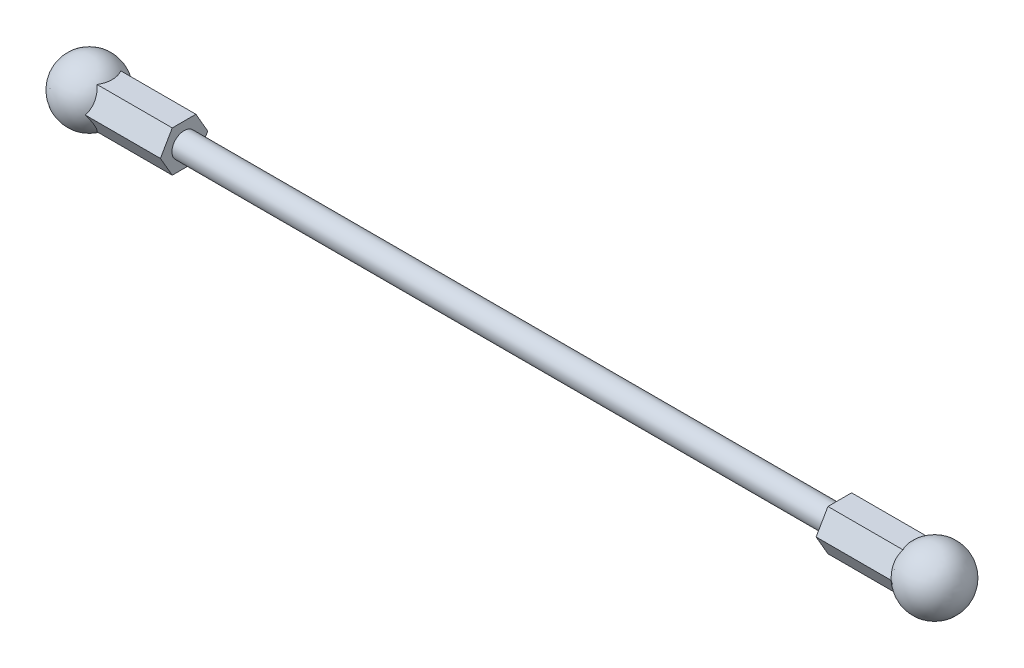
SolidWorks part; units mm, degrees
ref_plane "Front Plane" through (0, 0, 0) normal (0, 0, 1) x (1, 0, 0)
ref_plane "Top Plane" through (0, 0, 0) normal (0, 1, 0) x (1, 0, 0)
ref_plane "Right Plane" through (0, 0, 0) normal (1, 0, 0) x (0, 0, -1)
sketch "Sketch2" plane through (0, 0, 0) normal (0, 0, 1) x (1, 0, 0)
  line L5 (0, 3) -> (0, -3)
  arc A0 (0, 3) -> (0, -3) centre (0, 0) cw
  dimension "D3" = 3
revolve "Revolve1" add sketch "Sketch2" angle 360 about L5
ref_point "Point1"
ref_plane "Plane3" through (82.5, 0, 0) normal (1, 0, 0) x (0, 0, -1)
sketch "Sketch7" plane through (82.5, 0, 0) normal (1, 0, 0) x (0, 0, -1)
  line L0 (0, 3) -> (0, -3)
  circle A0 centre (0, 0) radius 3 construction
  arc A1 (0, 3) -> (0, -3) centre (0, 0) cw
revolve "Revolve2" add sketch "Sketch7" angle 360 about L0
ref_point "Point2"
sketch "Sketch3" plane through (0, 0, 0) normal (1, 0, 0) x (0, 0, -1)
  line L1 (1.1547, -2) -> (2.3094, 0)
  line L2 (2.3094, 0) -> (1.1547, 2)
  line L3 (1.1547, 2) -> (-1.1547, 2)
  line L4 (-1.1547, 2) -> (-2.3094, 0)
  line L5 (-2.3094, 0) -> (-1.1547, -2)
  line L6 (-1.1547, -2) -> (1.1547, -2)
  circle A0 centre (0, 0) radius 2 construction
  dimension "D1" = 4
extrude "Boss-Extrude2" add sketch "Sketch3" along normal blind 9.25 contours L4 L5 L6 L1 L2 L3
ref_plane "Plane4" through (41.25, 0, 0) normal (1, 0, 0) x (0, 0, -1)
mirror "Mirror3" about plane through (41.25, 0, 0) normal (1, 0, 0) of "Boss-Extrude2"
sketch "Sketch5" plane through (9.25, 0, 0) normal (1, 0, 0) x (0, 0, -1)
  line L0 (-2.3094, 0) -> (-1.1827, 0) construction
  circle A0 centre (0.0079, 0) radius 1.1906
  dimension "D1" = 2.3813
extrude "Boss-Extrude3" add sketch "Sketch5" along normal up to surface (64 mm away) up to face at (73.25, 0, 0)
